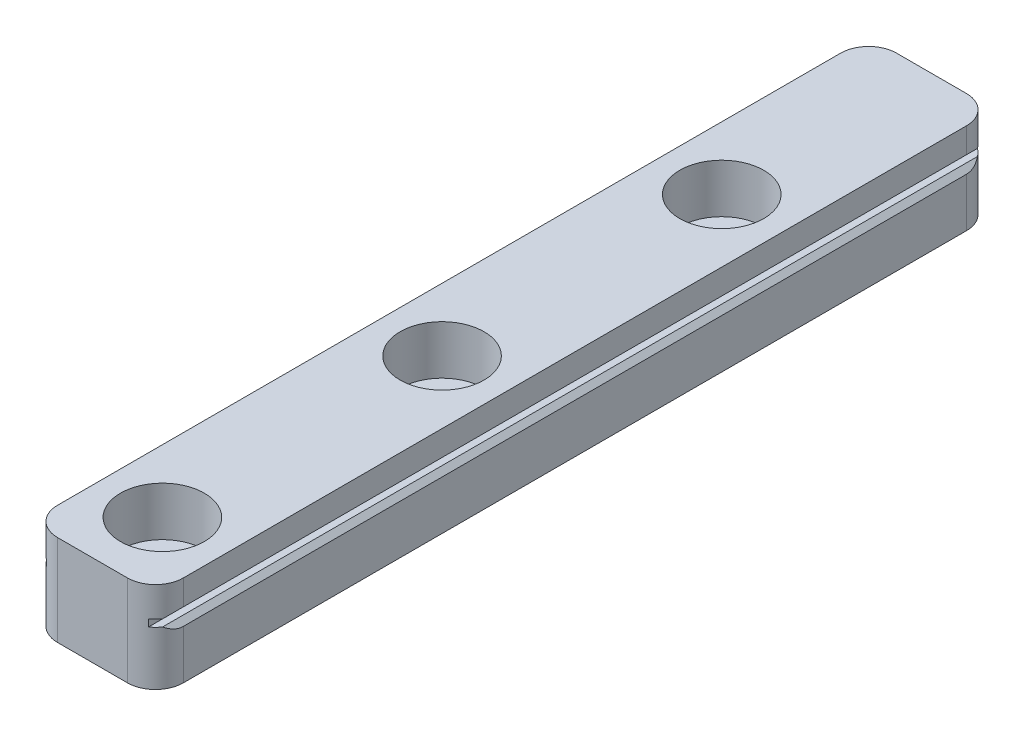
SolidWorks part; units mm, degrees
material "镀铬不锈钢"
ref_plane "前视基准面" through (0, 0, 0) normal (0, 0, 1) x (1, 0, 0)
ref_plane "上视基准面" through (0, 0, 0) normal (0, 1, 0) x (1, 0, 0)
ref_plane "右视基准面" through (0, 0, 0) normal (1, 0, 0) x (0, 0, -1)
sketch "草图2" plane through (0, 0, 0) normal (0, 0, 1) x (1, 0, 0)
  line L0 (0, 0) -> (9, 0)
  line L1 (4.5, 0) -> (4.5, 7.3268) construction
  line L2 (9, 0) -> (9, 3.5)
  line L3 (9, 3.5) -> (8.6464, 3.8536)
  line L4 (8.6464, 3.8536) -> (8.1464, 3.8536)
  line L5 (8.1464, 3.8536) -> (8.1464, 4.3536)
  line L6 (8.1464, 4.3536) -> (8.6464, 4.3536)
  line L7 (8.6464, 4.3536) -> (9, 4.7071)
  line L8 (9, 4.7071) -> (9, 6.5)
  line L9 (9, 6.5) -> (0, 6.5)
  line L10 (0, 4.7071) -> (0, 6.5)
  line L11 (0.3536, 4.3536) -> (0, 4.7071)
  line L12 (0.8536, 4.3536) -> (0.3536, 4.3536)
  line L13 (0.8536, 3.8536) -> (0.8536, 4.3536)
  line L14 (0.3536, 3.8536) -> (0.8536, 3.8536)
  line L15 (0, 3.5) -> (0.3536, 3.8536)
  line L16 (0, 0) -> (0, 3.5)
  point P14 (4.5, 6.5)
  dimension "D1" = 9
  dimension "D2" = 3.5
  dimension "D3" = 135
  dimension "D4" = 0.5
  dimension "D5" = 0.5
  dimension "D6" = 0.5
  dimension "D7" = 0.5
  dimension "D8" = 6.5
extrude "凸台-拉伸2" add sketch "草图2" against normal blind 60
sketch "草图3" plane through (0, 6.5, 0) normal (0, 1, 0) x (1, 0, 0)
  line L0 (9, 0) -> (0, 0) construction
  circle A0 centre (4.5, 5) radius 3
  circle A1 centre (4.5, 25) radius 3
  circle A2 centre (4.5, 45) radius 3
  circle A3 centre (4.5, 65) radius 3
  circle A4 centre (4.5, 85) radius 3
  circle A5 centre (4.5, 105) radius 3
  circle A6 centre (4.5, 125) radius 3
  circle A7 centre (4.5, 45) radius 3 [skipped]
  circle A8 centre (4.5, 65) radius 3 [skipped]
  circle A9 centre (4.5, 85) radius 3 [skipped]
  circle A10 centre (4.5, 105) radius 3 [skipped]
  circle A11 centre (4.5, 125) radius 3 [skipped]
  circle A16 centre (4.5, 145) radius 3
  circle A17 centre (4.5, 165) radius 3
  circle A18 centre (4.5, 185) radius 3
  circle A19 centre (4.5, 205) radius 3
  circle A20 centre (4.5, 225) radius 3
  circle A29 centre (4.5, 145) radius 3 [skipped]
  circle A30 centre (4.5, 165) radius 3 [skipped]
  circle A31 centre (4.5, 185) radius 3 [skipped]
  circle A32 centre (4.5, 205) radius 3 [skipped]
  circle A33 centre (4.5, 305) radius 3 [skipped]
  circle A34 centre (4.5, 325) radius 3 [skipped]
  circle A35 centre (4.5, 345) radius 3 [skipped]
  circle A36 centre (4.5, 365) radius 3 [skipped]
  circle A37 centre (4.5, 385) radius 3 [skipped]
  circle A38 centre (4.5, 265) radius 3 [skipped]
  circle A39 centre (4.5, 285) radius 3 [skipped]
  circle A40 centre (4.5, 245) radius 3 [skipped]
  point P2 (4.5, 0)
  dimension "D1" = 6
  dimension "D4" = 6
  dimension "D2" = 5
  dimension "D5" = 20
  dimension "D3" = 20
  dimension "D6" = 9
extrude "切除-拉伸1" cut sketch "草图3" against normal blind 3.5
sketch "草图4" plane through (0, 3, 0) normal (0, 1, 0) x (1, 0, 0)
  circle A0 centre (4.5, 5) radius 1.75
  circle A1 centre (4.5, 25) radius 1.75
  circle A2 centre (4.5, 45) radius 1.75
  circle A3 centre (4.5, 65) radius 1.75
  circle A4 centre (4.5, 85) radius 1.75
  circle A5 centre (4.5, 105) radius 1.75
  circle A6 centre (4.5, 125) radius 1.75
  circle A7 centre (4.5, 65) radius 1.75 [skipped]
  circle A8 centre (4.5, 85) radius 1.75 [skipped]
  circle A9 centre (4.5, 105) radius 1.75 [skipped]
  circle A10 centre (4.5, 125) radius 1.75 [skipped]
  circle A11 centre (4.5, 45) radius 1.75 [skipped]
  circle A12 centre (4.5, 145) radius 1.75
  circle A13 centre (4.5, 165) radius 1.75
  circle A14 centre (4.5, 185) radius 1.75
  circle A15 centre (4.5, 205) radius 1.75
  circle A16 centre (4.5, 225) radius 1.75
  circle A25 centre (4.5, 265) radius 1.75 [skipped]
  circle A26 centre (4.5, 285) radius 1.75 [skipped]
  circle A27 centre (4.5, 305) radius 1.75 [skipped]
  circle A28 centre (4.5, 325) radius 1.75 [skipped]
  circle A29 centre (4.5, 345) radius 1.75 [skipped]
  circle A30 centre (4.5, 365) radius 1.75 [skipped]
  circle A31 centre (4.5, 385) radius 1.75 [skipped]
  circle A32 centre (4.5, 245) radius 1.75 [skipped]
  dimension "D1" = 3.5
  dimension "D3" = 3.5
  dimension "D2" = 7
  dimension "D4" = 18
extrude "切除-拉伸2" cut sketch "草图4" against normal up to surface (3 mm away) up to face at (4.5, 0, -30)
fillet "圆角1" radius 2 4 edges at (9, 1.75, -60) (0, 1.75, -60) (9, 1.75, 0) (0, 1.75, 0)
